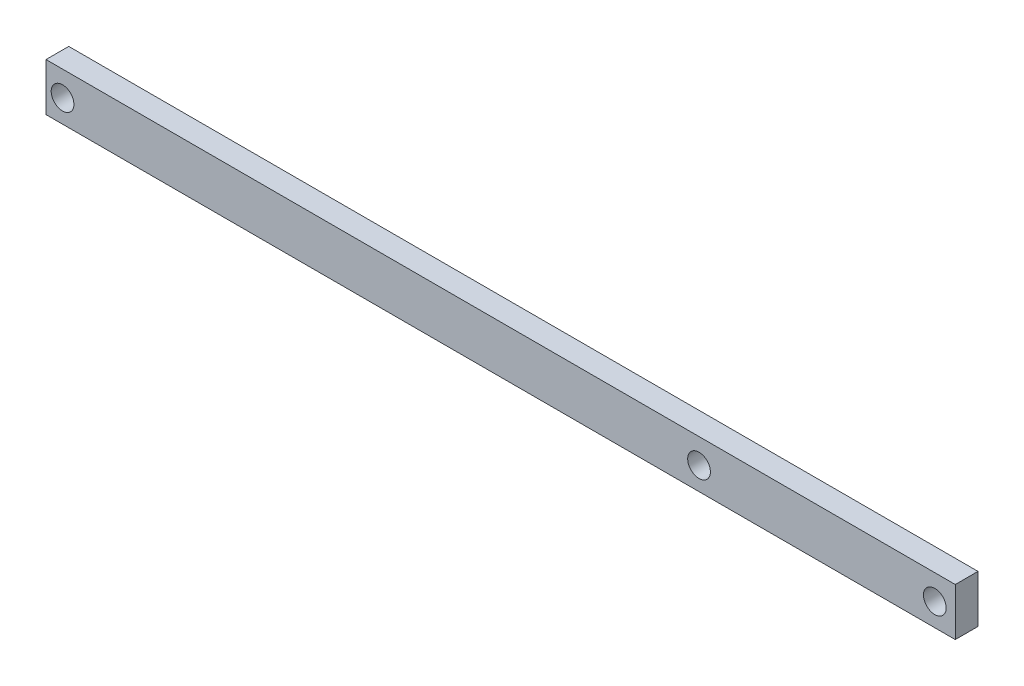
SolidWorks part; units mm, degrees
ref_plane "前视基准面" through (0, 0, 0) normal (0, 0, 1) x (1, 0, 0)
ref_plane "上视基准面" through (0, 0, 0) normal (0, 1, 0) x (1, 0, 0)
ref_plane "右视基准面" through (0, 0, 0) normal (1, 0, 0) x (0, 0, -1)
sketch "草图1" plane through (0, 0, 0) normal (0, 0, 1) x (1, 0, 0)
  line L1 (-116.3002, 8.6544) -> (283.6998, 8.6544)
  line L2 (-116.3002, 8.6544) -> (-116.3002, -12.3386)
  line L3 (-116.3002, -12.3386) -> (283.6998, -12.3386)
  line L4 (283.6998, 8.6544) -> (283.6998, -12.3386)
  circle A0 centre (-109.0203, -2.3185) radius 5
  circle A1 centre (170.9797, -2.3211) radius 5
  circle A2 centre (274.7041, -2.3211) radius 5
  point P10 (274.7041, -2.3211)
  dimension "D1" = 280
  dimension "D2" = 400
extrude "凸台-拉伸1" add sketch "草图1" along normal blind 10
